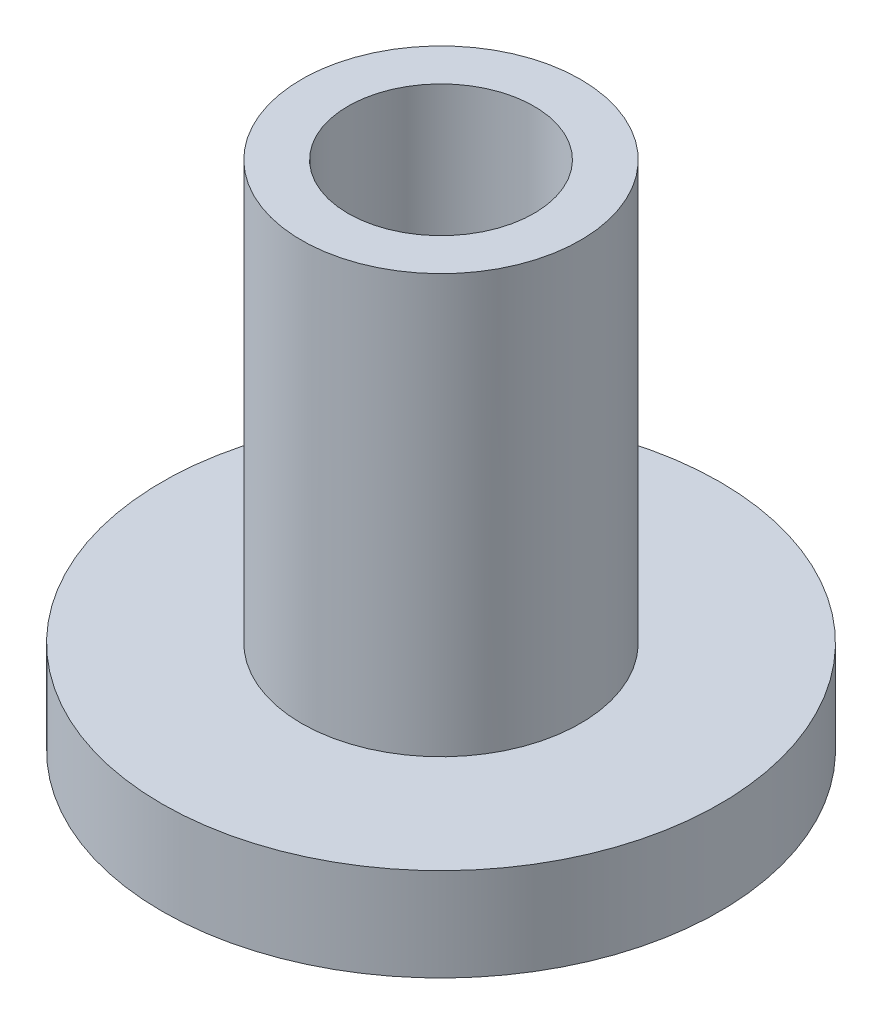
SolidWorks part; units mm, degrees
ref_plane "Front Plane" through (0, 0, 0) normal (0, 0, 1) x (1, 0, 0)
ref_plane "Top Plane" through (0, 0, 0) normal (0, 1, 0) x (1, 0, 0)
ref_plane "Right Plane" through (0, 0, 0) normal (1, 0, 0) x (0, 0, -1)
sketch "Sketch1" plane through (0, 0, 0) normal (0, 1, 0) x (1, 0, 0)
  circle A0 centre (0, 0) radius 38.1
  circle A1 centre (0, 0) radius 19.05
  circle A2 centre (0, 0) radius 12.7
extrude "Boss-Extrude1" add sketch "Sketch1" along normal blind 12.7 contours A0 A1
sketch "Sketch2" plane through (0, 0, 0) normal (0, -1, 0) x (1, 0, 0)
  circle A0 centre (0, 0) radius 19.05
extrude "Boss-Extrude3" add sketch "Sketch2" against normal blind 69.85
sketch "Sketch3" plane through (0, 69.85, 0) normal (0, 1, 0) x (1, 0, 0)
  circle A0 centre (0, 0) radius 12.7
extrude "Cut-Extrude1" cut sketch "Sketch3" against normal blind 69.85
